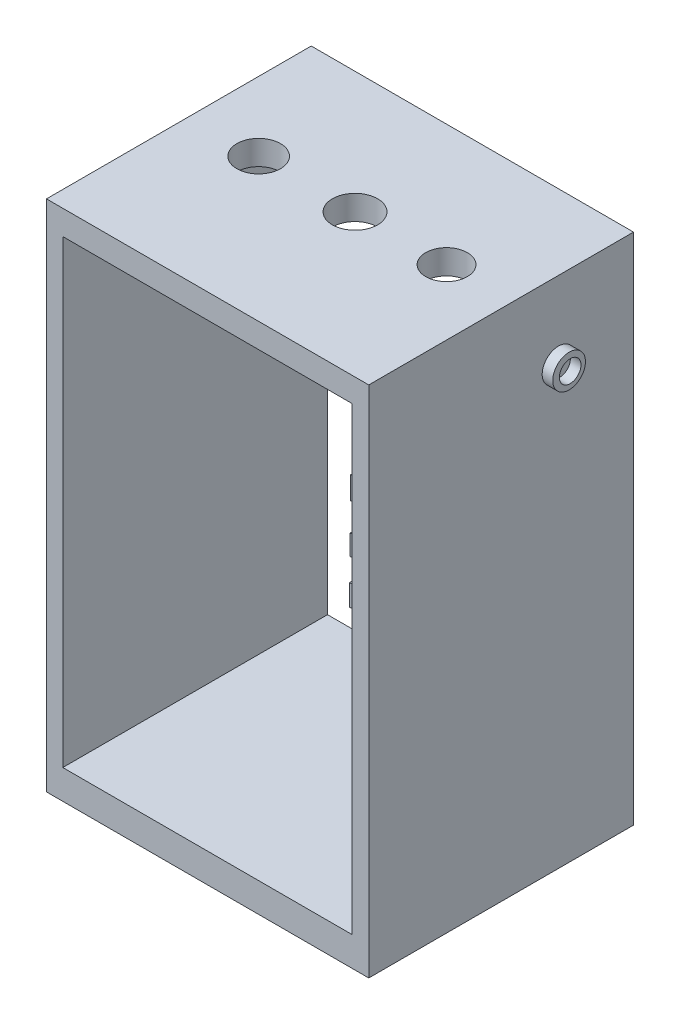
SolidWorks part; units mm, degrees
ref_plane "Front Plane" through (0, 0, 0) normal (0, 0, 1) x (1, 0, 0)
ref_plane "Top Plane" through (0, 0, 0) normal (0, 1, 0) x (1, 0, 0)
ref_plane "Right Plane" through (0, 0, 0) normal (1, 0, 0) x (0, 0, -1)
sketch "Sketch1" plane through (0, 0, 0) normal (0, 0, 1) x (1, 0, 0)
  line L1 (-30.4309, 48.4986) -> (30.4309, 48.4986)
  line L2 (-30.4309, 48.4986) -> (-30.4309, -48.4986)
  line L3 (-30.4309, -48.4986) -> (30.4309, -48.4986)
  line L4 (30.4309, 48.4986) -> (30.4309, -48.4986)
  line L5 (-30.4309, 48.4986) -> (30.4309, -48.4986) construction
  line L6 (-30.4309, -48.4986) -> (30.4309, 48.4986) construction
  point P0 (0, 0)
extrude "Boss-Extrude1" add sketch "Sketch1" along normal blind 50
sketch "Sketch2" plane through (0, 0, 50) normal (0, 0, 1) x (1, 0, 0)
  line L1 (-27.353, 43.8756) -> (27.2441, 43.8756)
  line L2 (-27.353, 43.8756) -> (-27.353, -42.9682)
  line L3 (-27.353, -42.9682) -> (27.2441, -42.9682)
  line L4 (27.2441, 43.8756) -> (27.2441, -42.9682)
  line L5 (-27.353, 43.8756) -> (27.2441, -42.9682) construction
  line L6 (-27.353, -42.9682) -> (27.2441, 43.8756) construction
  point P0 (-0.0545, 0.4537)
extrude "Cut-Extrude1" cut sketch "Sketch2" against normal blind 50
sketch "Sketch3" plane through (0, 48.4986, 0) normal (0, 1, 0) x (1, 0, 0)
  circle A0 centre (-17.3796, -22.9819) radius 4.1182
  circle A1 centre (0.8163, -22.9819) radius 4.2728
  circle A2 centre (18.0989, -22.9819) radius 3.9327
extrude "Cut-Extrude2" cut sketch "Sketch3" against normal blind 6
sketch "Sketch4" plane through (30.4309, 0, 0) normal (1, 0, 0) x (0, 0, -1)
  circle A0 centre (-14.1634, 33.8493) radius 3.0877
extrude "Boss-Extrude2" add sketch "Sketch4" along normal blind 2
sketch "Sketch5" plane through (32.4309, 0, 0) normal (1, 0, 0) x (0, 0, -1)
  circle A0 centre (-13.9619, 33.7344) radius 2.0382
extrude "Cut-Extrude3" cut sketch "Sketch5" against normal blind 2
sketch "Sketch6" plane through (-30.4309, 0, 0) normal (-1, 0, 0) x (0, 0, 1)
  circle A0 centre (13.1796, 35.996) radius 3.9087
  circle A1 centre (13.1796, 35.996) radius 2.5351
extrude "Boss-Extrude3" add sketch "Sketch6" along normal blind 2
sketch "Sketch7" plane through (-30.4309, 0, 0) normal (-1, 0, 0) x (0, 0, 1)
  circle A0 centre (13.1796, 35.996) radius 2.2194
extrude "Cut-Extrude4" cut sketch "Sketch7" against normal blind 2
sketch "Sketch8" plane through (27.2441, 0, 0) normal (-1, 0, 0) x (0, 0, 1)
  line L1 (0.8242, 26.0609) -> (48.2196, 26.0609)
  line L2 (0.8242, 26.0609) -> (0.8242, 30.3525)
  line L3 (0.8242, 30.3525) -> (48.2196, 30.3525)
  line L4 (48.2196, 26.0609) -> (48.2196, 30.3525)
  line L5 (0.8242, 26.0609) -> (48.2196, 30.3525) construction
  line L6 (0.8242, 30.3525) -> (48.2196, 26.0609) construction
  line L7 (2.1122, 17.0248) -> (48.3472, 17.0248)
  line L8 (2.1122, 17.0248) -> (2.1122, 20.8672)
  line L9 (2.1122, 20.8672) -> (48.3472, 20.8672)
  line L10 (48.3472, 17.0248) -> (48.3472, 20.8672)
  line L11 (2.1122, 17.0248) -> (48.3472, 20.8672) construction
  line L12 (2.1122, 20.8672) -> (48.3472, 17.0248) construction
  line L13 (2.0005, 12.7952) -> (48.4589, 12.7952)
  line L14 (2.0005, 12.7952) -> (2.0005, 8.7814)
  line L15 (2.0005, 8.7814) -> (48.4589, 8.7814)
  line L16 (48.4589, 12.7952) -> (48.4589, 8.7814)
  line L17 (2.0005, 12.7952) -> (48.4589, 8.7814) construction
  line L18 (2.0005, 8.7814) -> (48.4589, 12.7952) construction
  line L19 (1.2495, 4.7625) -> (46.066, 4.7625)
  line L20 (1.2495, 4.7625) -> (1.2495, 1.0035)
  line L21 (1.2495, 1.0035) -> (46.066, 1.0035)
  line L22 (46.066, 4.7625) -> (46.066, 1.0035)
  line L23 (1.2495, 4.7625) -> (46.066, 1.0035) construction
  line L24 (1.2495, 1.0035) -> (46.066, 4.7625) construction
  line L25 (1.7331, -3.2415) -> (46.066, -3.2415)
  line L26 (1.7331, -3.2415) -> (1.7331, -6.7856)
  line L27 (1.7331, -6.7856) -> (46.066, -6.7856)
  line L28 (46.066, -3.2415) -> (46.066, -6.7856)
  line L29 (1.7331, -3.2415) -> (46.066, -6.7856) construction
  line L30 (1.7331, -6.7856) -> (46.066, -3.2415) construction
  line L31 (2.2306, -11.3633) -> (46.066, -11.3633)
  line L32 (2.2306, -11.3633) -> (2.2306, -16.2162)
  line L33 (2.2306, -16.2162) -> (46.066, -16.2162)
  line L34 (46.066, -11.3633) -> (46.066, -16.2162)
  line L35 (2.2306, -11.3633) -> (46.066, -16.2162) construction
  line L36 (2.2306, -16.2162) -> (46.066, -11.3633) construction
  line L37 (1.834, -20.0693) -> (46.066, -20.0693)
  line L38 (1.834, -20.0693) -> (1.834, -23.6553)
  line L39 (1.834, -23.6553) -> (46.066, -23.6553)
  line L40 (46.066, -20.0693) -> (46.066, -23.6553)
  line L41 (1.834, -20.0693) -> (46.066, -23.6553) construction
  line L42 (1.834, -23.6553) -> (46.066, -20.0693) construction
  line L43 (1.8809, -34.0258) -> (46.3833, -34.0258)
  line L44 (1.8809, -34.0258) -> (1.8809, -28.4885)
  line L45 (1.8809, -28.4885) -> (46.3833, -28.4885)
  line L46 (46.3833, -34.0258) -> (46.3833, -28.4885)
  line L47 (1.8809, -34.0258) -> (46.3833, -28.4885) construction
  line L48 (1.8809, -28.4885) -> (46.3833, -34.0258) construction
  point P0 (24.5219, 28.2067)
  point P5 (23.6578, 2.883)
  point P6 (25.2297, 18.946)
  point P11 (25.2297, 10.7883)
  point P20 (23.95, -21.8623)
  point P21 (24.1483, -13.7897)
  point P22 (23.8996, -5.0136)
  point P35 (24.1321, -31.2572)
extrude "Boss-Extrude4" add sketch "Sketch8" along normal blind 2
sketch "Sketch9" plane through (27.2441, 0, 0) normal (-1, 0, 0) x (0, 0, 1)
  line L1 (2.515, 37.863) -> (47.2451, 37.863)
  line L2 (2.515, 37.863) -> (2.515, 33.6562)
  line L3 (2.515, 33.6562) -> (47.2451, 33.6562)
  line L4 (47.2451, 37.863) -> (47.2451, 33.6562)
  line L5 (2.515, 37.863) -> (47.2451, 33.6562) construction
  line L6 (2.515, 33.6562) -> (47.2451, 37.863) construction
  line L7 (1.8451, -36.5628) -> (45.5771, -36.5628)
  line L8 (1.8451, -36.5628) -> (1.8451, -41.0826)
  line L9 (1.8451, -41.0826) -> (45.5771, -41.0826)
  line L10 (45.5771, -36.5628) -> (45.5771, -41.0826)
  line L11 (1.8451, -36.5628) -> (45.5771, -41.0826) construction
  line L12 (1.8451, -41.0826) -> (45.5771, -36.5628) construction
  point P0 (24.88, 35.7596)
  point P5 (23.7111, -38.8227)
extrude "Boss-Extrude5" add sketch "Sketch9" along normal blind 2
